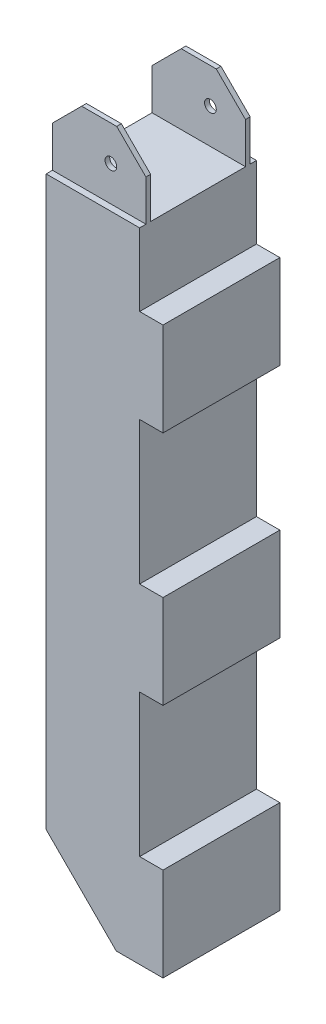
SolidWorks part; units mm, degrees
ref_plane "Front Plane" through (0, 0, 0) normal (0, 0, 1) x (1, 0, 0)
ref_plane "Top Plane" through (0, 0, 0) normal (0, 1, 0) x (1, 0, 0)
ref_plane "Right Plane" through (0, 0, 0) normal (1, 0, 0) x (0, 0, -1)
sketch "Sketch1" plane through (0, 0, 0) normal (0, 0, 1) x (1, 0, 0)
  line L0 (0, 0) -> (0, -100) construction
  line L1 (0, -100) -> (-5, -100)
  line L2 (0, -100) -> (0, -40)
  line L3 (0, -40) -> (-0.2, -40)
  line L4 (-3, -37.2) -> (-3, 0)
  line L5 (-3, 0) -> (-27, 0)
  line L6 (-27, 0) -> (-27, -5)
  line L7 (-27, -5) -> (-12, -5)
  line L8 (-12, -5) -> (-5, -60)
  line L9 (-5, -60) -> (-5, -100)
  line L10 (0, 0) -> (-3, 0) construction
  arc A0 (-0.2, -40) -> (-3, -37.2) centre (-0.2, -37.2) cw
  point P16 (-3, -40)
  dimension "D6" = 2.8
  dimension "D1" = 100
  dimension "D2" = 60
  dimension "D3" = 5
  dimension "D4" = 3
  dimension "D5" = 24
  dimension "D7" = 5
  dimension "D8" = 15
  dimension "D9" = 40
extrude "Boss-Extrude1" add sketch "Sketch1" along normal blind 5
sketch "Sketch4" plane through (0, 0, 0) normal (1, 0, 0) x (0, 0, -1)
  line L0 (-5, -100) -> (-5, -40) construction
  line L1 (-5, -96) -> (0, -96)
  line L2 (-5, -96) -> (-5, -89.9)
  line L3 (-5, -89.9) -> (0, -89.9)
  line L4 (0, -96) -> (0, -89.9)
  line L5 (0, -100) -> (0, -40) construction
  line L6 (-5, -100) -> (0, -100) construction
  line L7 (-5, -79.8) -> (0, -79.8)
  line L8 (-5, -85.9) -> (0, -85.9)
  line L9 (0, -85.9) -> (0, -79.8)
  line L10 (-5, -85.9) -> (-5, -79.8)
  line L11 (-5, -69.7) -> (0, -69.7)
  line L12 (-5, -75.8) -> (0, -75.8)
  line L13 (0, -75.8) -> (0, -69.7)
  line L14 (-5, -75.8) -> (-5, -69.7)
  line L15 (-5, -59.6) -> (0, -59.6)
  line L16 (-5, -65.7) -> (0, -65.7)
  line L17 (0, -65.7) -> (0, -59.6)
  line L18 (-5, -65.7) -> (-5, -59.6)
  line L19 (-5, -49.5) -> (0, -49.5)
  line L20 (-5, -55.6) -> (0, -55.6)
  line L21 (0, -55.6) -> (0, -49.5)
  line L22 (-5, -55.6) -> (-5, -49.5)
  line L23 (-5, -39.4) -> (0, -39.4)
  line L24 (-5, -45.5) -> (0, -45.5)
  line L25 (0, -45.5) -> (0, -39.4)
  line L26 (-5, -45.5) -> (-5, -39.4)
  dimension "D1" = 4
  dimension "D2" = 6.1
  dimension "D3" = 6
extrude "Cut-Extrude1" cut sketch "Sketch4" against normal blind 1
chamfer "Chamfer1" distance 3 angle 45 1 edges at (-5, -100, 2.5)
sketch "Sketch9" plane through (0, 0, 5) normal (0, 0, 1) x (1, 0, 0)
  line L0 (-1, -69.7) -> (-5, -69.7)
  line L1 (-5, -60) -> (-5, -97) construction
extrude "Cut-Extrude8" cut sketch "Sketch9" against normal through all and the other way through all flip side to cut
sketch "Sketch13" plane through (0, 0, 5) normal (0, 0, 1) x (1, 0, 0)
  line L0 (-1, -69.7) -> (-1, -72.7) construction
  line L1 (-1, -69.7) -> (-1, -75.8) construction
  circle A0 centre (-2.5, -71.2) radius 0.25
  dimension "D2" = 0.5
  dimension "D1" = 3
extrude "Cut-Extrude9" cut sketch "Sketch13" against normal through all
sketch "Sketch14" plane through (-1, 0, 0) normal (1, 0, 0) x (0, 0, -1)
  line L0 (-5, -69.7) -> (-4.73, -69.7) construction
  line L1 (0, -69.7) -> (-5, -69.7) construction
  line L2 (0, -69.7) -> (-0.27, -69.7) construction
  line L3 (-4.73, -69.7) -> (-4.73, -72.7) construction
  line L4 (-4.73, -72.7) -> (-5, -72.7) construction
  line L5 (-5, -69.7) -> (-5, -75.8) construction
  line L6 (-0.27, -69.7) -> (-0.27, -72.7) construction
  line L7 (-5, -69.7) -> (-4.73, -69.7)
  line L8 (-5, -69.7) -> (-5, -72.7)
  line L9 (-5, -72.7) -> (-4.73, -72.7)
  line L10 (-4.73, -69.7) -> (-4.73, -72.7)
  line L11 (-0.27, -72.7) -> (0, -72.7) construction
  line L12 (0, -75.8) -> (0, -69.7) construction
  line L14 (-0.27, -69.7) -> (0, -69.7)
  line L15 (-0.27, -69.7) -> (-0.27, -72.7)
  line L16 (-0.27, -72.7) -> (0, -72.7)
  line L17 (0, -69.7) -> (0, -72.7)
  dimension "D1" = 0.27
  dimension "D2" = 3
extrude "Cut-Extrude11" cut sketch "Sketch14" against normal through all
sketch "Sketch16" plane through (-1, 0, 0) normal (1, 0, 0) x (0, 0, -1)
  line L0 (-4.73, -69.7) -> (-4.53, -69.7) construction
  line L1 (-0.27, -69.7) -> (-4.73, -69.7) construction
  line L2 (-0.27, -69.7) -> (-0.47, -69.7) construction
  line L3 (-4.53, -69.7) -> (-4.53, -72.7)
  line L4 (-4.53, -72.7) -> (-0.47, -72.7)
  line L5 (-0.47, -72.7) -> (-0.47, -69.7)
  line L6 (-0.47, -69.7) -> (-4.53, -69.7)
  dimension "D1" = 0.2
  dimension "D2" = 3
  dimension "D3" = 3
  dimension "D4" = 4.06
extrude "Cut-Extrude12" cut sketch "Sketch16" against normal through all
chamfer "Chamfer4" distance 1.25 angle 45 1 edges at (-1, -69.7, 4.63)
chamfer "Chamfer7" distance 1.25 angle 45 1 edges at (-1, -69.7, 0.37)
chamfer "Chamfer8" distance 1.25 angle 45 1 edges at (-5, -69.7, 4.63)
chamfer "Chamfer9" distance 1.25 angle 45 1 edges at (-5, -69.7, 0.37)
